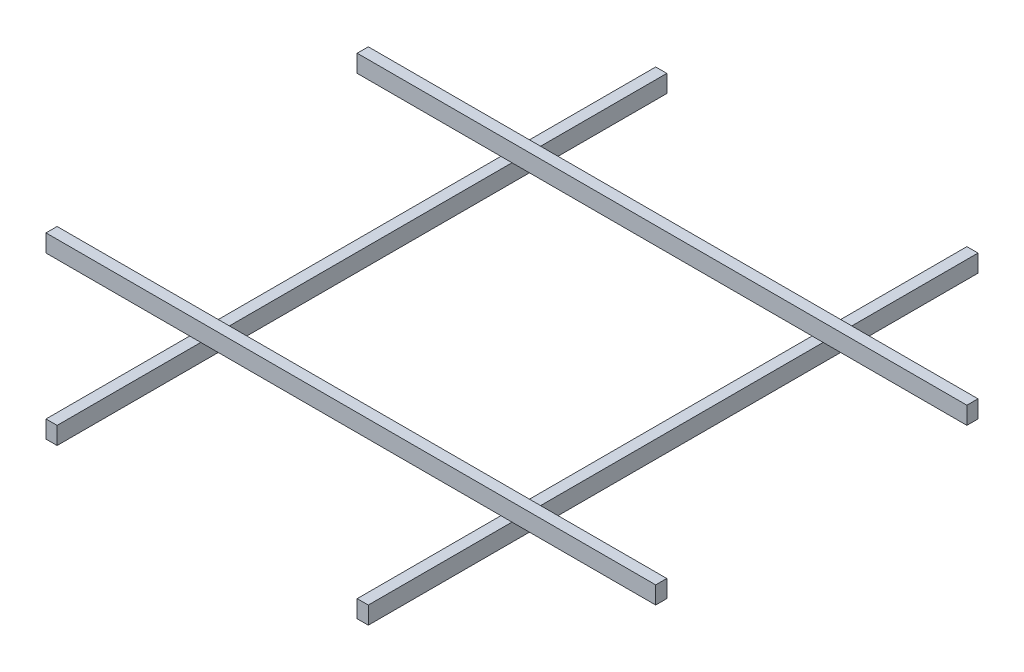
SolidWorks part; units mm, degrees
material "Doug Fir"
ref_plane "Front Plane" through (0, 0, 0) normal (0, 0, 1) x (1, 0, 0)
ref_plane "Top Plane" through (0, 0, 0) normal (0, 1, 0) x (1, 0, 0)
ref_plane "Right Plane" through (0, 0, 0) normal (1, 0, 0) x (0, 0, -1)
sketch "Lower Level" plane through (0, 0, 0) normal (0, 1, 0) x (1, 0, 0)
  line L0 (889, 0) -> (889, 4876.8)
  line L1 (3378.2, 0) -> (3378.2, 4876.8)
  line L2 (889, 2438.4) -> (3378.2, 2438.4) construction
  point P7 (2133.6, 2438.4)
  dimension "D1" = 4876.8
  dimension "D2" = 1244.6
ref_plane "Plane2" through (0, 139.7, 0) normal (0, 1, 0) x (1, 0, 0)
sketch "Sketch12" plane through (0, 139.7, 0) normal (0, 1, 0) x (1, 0, 0)
  line L0 (-304.8, 3683) -> (4572, 3683)
  line L1 (4572, 1193.8) -> (-304.8, 1193.8)
  line L2 (2133.6, 3683) -> (2133.6, 1193.8) construction
  point P0 (2133.6, 2438.4)
  point P6 (2133.6, 1193.8)
  point P7 (2133.6, 3683)
  point P10 (2133.6, 2438.4)
  dimension "D1" = 4876.8
  dimension "D2" = 1244.6
other "Profiles 4X6(1)"
ref_plane "Plane1" through (889, 0, 0) normal (0, 0, -1) x (-1, 0, 0)
sketch "Sketch1" plane through (889, 0, 0) normal (0, 0, -1) x (-1, 0, 0)
  line L1 (-44.45, 69.85) -> (44.45, 69.85)
  line L2 (-44.45, 69.85) -> (-44.45, -69.85)
  line L3 (-44.45, -69.85) -> (44.45, -69.85)
  line L4 (44.45, 69.85) -> (44.45, -69.85)
  line L5 (-44.45, 69.85) -> (44.45, -69.85) construction
  line L6 (-44.45, -69.85) -> (44.45, 69.85) construction
  point P0 (0, 0)
  point P6 (0, 69.85)
  point P7 (0, -69.85)
  point P8 (44.45, 0)
  point P9 (-44.45, 0)
  point P10 (0, 0)
  dimension "D1" = 88.9
  dimension "D2" = 139.7
sketch3d "3DSketch2"
  line L0 (2133.6, 139.7, -2438.4) -> (2133.6, 0, -2438.4)
  line L1 (889, 0, -2438.4) -> (3378.2, 0, -2438.4) construction
equation "\"Width\" = 49"
equation "\"Length\"=192"
equation "\"D1@Lower Level\"=\"Length\""
equation "\"D2@Lower Level\"=\"Width\""
equation "\"D1@Sketch12\"=\"Length\""
equation "\"D2@Sketch12\"=\"Width\""
